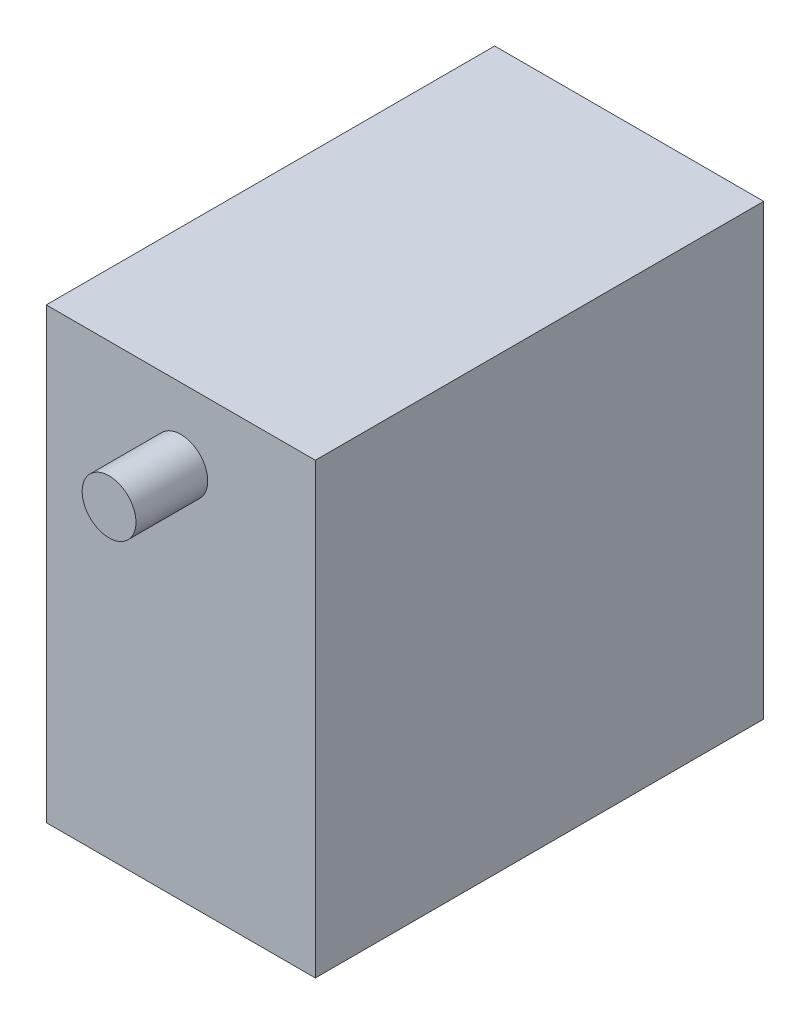
SolidWorks part; units mm, degrees
ref_plane "前视基准面" through (0, 0, 0) normal (0, 0, 1) x (1, 0, 0)
ref_plane "上视基准面" through (0, 0, 0) normal (0, 1, 0) x (1, 0, 0)
ref_plane "右视基准面" through (0, 0, 0) normal (1, 0, 0) x (0, 0, -1)
sketch "草图1" plane through (0, 0, 0) normal (0, 0, 1) x (1, 0, 0)
  line L1 (-15, -25) -> (15, -25)
  line L2 (-15, -25) -> (-15, 25)
  line L3 (-15, 25) -> (15, 25)
  line L4 (15, -25) -> (15, 25)
  line L5 (-15, -25) -> (15, 25) construction
  line L6 (-15, 25) -> (15, -25) construction
  point P0 (0, 0)
  dimension "D1" = 30
  dimension "D2" = 50
extrude "凸台-拉伸1" add sketch "草图1" along normal blind 50
sketch "草图2" plane through (0, 0, 50) normal (0, 0, 1) x (1, 0, 0)
  line L0 (0, 25) -> (0, -25) construction
  line L1 (15, 25) -> (-15, 25) construction
  line L2 (-15, -25) -> (15, -25) construction
  circle A0 centre (0, 17) radius 3
  dimension "D1" = 6
  dimension "D2" = 8
extrude "凸台-拉伸2" add sketch "草图2" along normal blind 8
